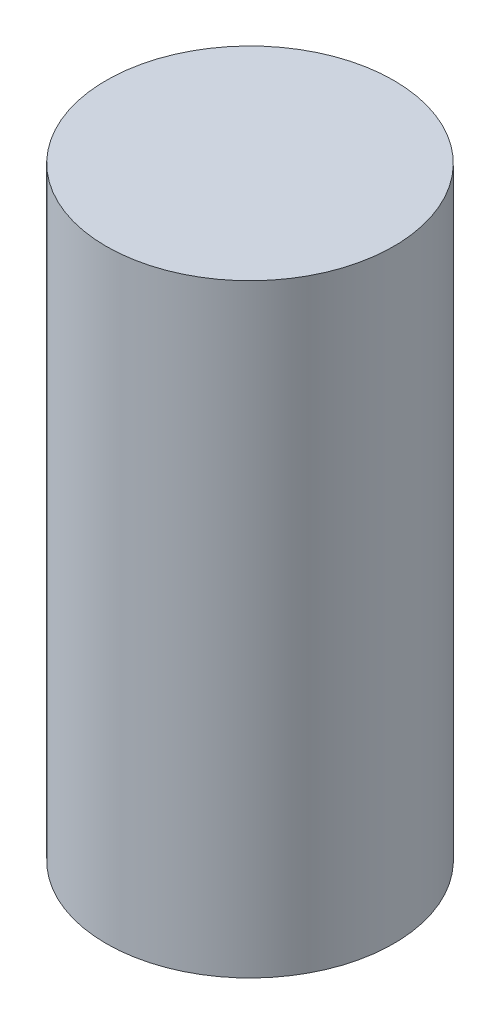
SolidWorks part; units mm, degrees
ref_plane "Front Plane" through (0, 0, 0) normal (0, 0, 1) x (1, 0, 0)
ref_plane "Top Plane" through (0, 0, 0) normal (0, 1, 0) x (1, 0, 0)
ref_plane "Right Plane" through (0, 0, 0) normal (1, 0, 0) x (0, 0, -1)
sketch "Sketch1" plane through (0, 0, 0) normal (0, 1, 0) x (1, 0, 0)
  circle A0 centre (0, 0) radius 2
  point P3 (0, 0)
  dimension "D1" = 4
extrude "Boss-Extrude1" add sketch "Sketch1" along normal blind 8.4
